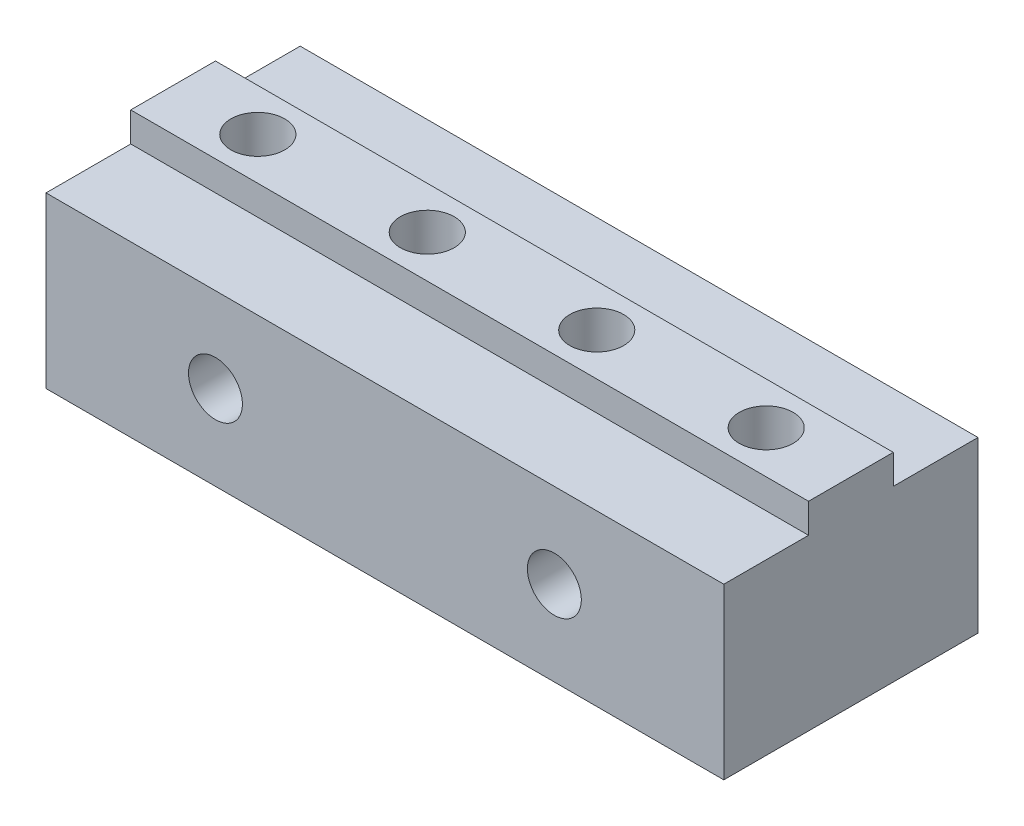
SolidWorks part; units mm, degrees
ref_plane "Front Plane" through (0, 0, 0) normal (0, 0, 1) x (1, 0, 0)
ref_plane "Top Plane" through (0, 0, 0) normal (0, 1, 0) x (1, 0, 0)
ref_plane "Right Plane" through (0, 0, 0) normal (1, 0, 0) x (0, 0, -1)
sketch "Sketch1" plane through (0, 0, 0) normal (0, 1, 0) x (1, 0, 0)
  line L1 (25.4, -9.525) -> (-25.4, -9.525)
  line L2 (25.4, -9.525) -> (25.4, 9.525)
  line L3 (25.4, 9.525) -> (-25.4, 9.525)
  line L4 (-25.4, -9.525) -> (-25.4, 9.525)
  line L5 (25.4, -9.525) -> (-25.4, 9.525) construction
  line L6 (25.4, 9.525) -> (-25.4, -9.525) construction
  point P0 (0, 0)
  dimension "D1" = 50.8
  dimension "D2" = 19.05
extrude "Boss-Extrude1" add sketch "Sketch1" along normal blind 12.7
sketch "Sketch2" plane through (0, 12.7, 0) normal (0, 1, 0) x (1, 0, 0)
  line L0 (-25.4, 9.525) -> (-25.4, -9.525) construction
  line L1 (25.4, -3.175) -> (-25.4, -3.175)
  line L2 (25.4, -3.175) -> (25.4, 3.175)
  line L3 (25.4, 3.175) -> (-25.4, 3.175)
  line L4 (-25.4, -3.175) -> (-25.4, 3.175)
  line L5 (25.4, -3.175) -> (-25.4, 3.175) construction
  line L6 (25.4, 3.175) -> (-25.4, -3.175) construction
  point P0 (0, 0)
  dimension "D1" = 6.35
extrude "Boss-Extrude2" add sketch "Sketch2" along normal blind 2.2098
hole_wizard "#10-32 Tapped Hole1" positions "Sketch3" profile "Sketch4" tap size "#10-32" standard "ANSI Inch" end condition through all
sketch "Sketch3" plane through (0, 0, -9.525) normal (0, 0, -1) x (-1, 0, 0)
  line L0 (-25.4, 6.35) -> (25.4, 6.35) construction
  line L1 (-25.4, 12.7) -> (-25.4, 0) construction
  line L2 (25.4, 12.7) -> (25.4, 0) construction
  point P9 (-12.7, 6.35)
  point P11 (12.7, 6.35)
  dimension "D1" = 12.7
  dimension "D2" = 12.7
sketch "Sketch4" plane through (-12.7, 6.35, -9.525) normal (1, 0, 0) x (0, 1, 0)
  line L0 (0, 0) -> (0, 19.05)
  line L1 (0, 19.05) -> (2.0193, 19.05)
  line L2 (2.0193, 19.05) -> (2.0193, 0)
  line L5 (2.0193, 0) -> (0, 0)
  line L11 (0, -6.35) -> (0, 107.95) construction
  dimension "Thread Major Dia." = 4.0386
  dimension "Thru Tap Drill Depth" = 19.05
hole_wizard "#10-32 Tapped Hole2" positions "Sketch5" profile "Sketch6" tap size "#10-32" standard "ANSI Inch" end condition through all
sketch "Sketch5" plane through (0, 0, 0) normal (0, -1, 0) x (-1, 0, 0)
  line L0 (-25.4, 0) -> (25.4, 0) construction
  line L1 (-25.4, -9.525) -> (-25.4, 9.525) construction
  line L2 (25.4, 9.525) -> (25.4, -9.525) construction
  point P10 (19.05, 0)
  point P12 (6.35, 0)
  point P14 (-6.35, 0)
  point P16 (-19.05, 0)
  point P20 (5.8971, 0)
  point P21 (0, 0)
  point P22 (-6.8096, 0)
  point P23 (-6.0561, 0)
  dimension "D1" = 12.7
  dimension "D2" = 12.7
  dimension "D3" = 6.35
  dimension "D4" = 6.35
sketch "Sketch6" plane through (19.05, 0, 0) normal (1, 0, 0) x (0, 0, -1)
  line L0 (0, 0) -> (0, 14.9098)
  line L1 (0, 14.9098) -> (2.0193, 14.9098)
  line L2 (2.0193, 14.9098) -> (2.0193, 0)
  line L5 (2.0193, 0) -> (0, 0)
  line L11 (0, -6.35) -> (0, 107.95) construction
  dimension "Thread Major Dia." = 4.0386
  dimension "Thru Tap Drill Depth" = 14.9098
